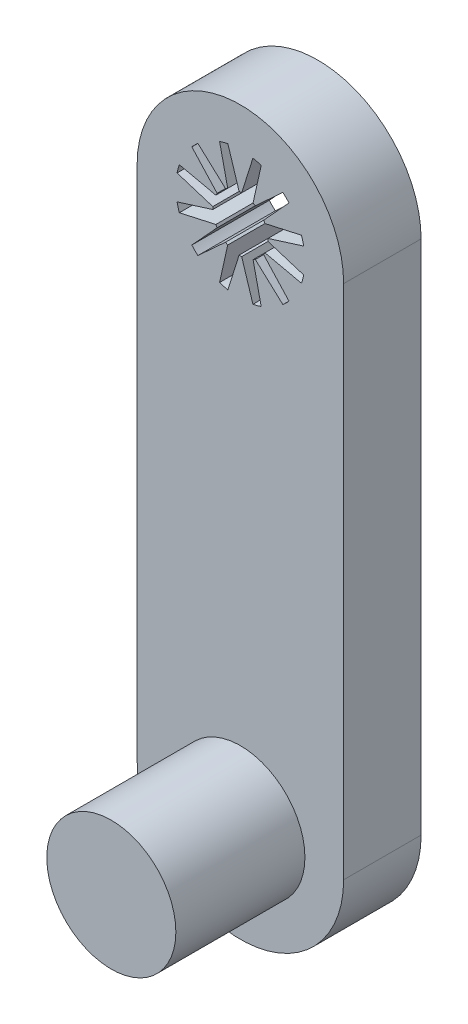
SolidWorks part; units mm, degrees
ref_plane "Front Plane" through (0, 0, 0) normal (1, 0, 0) x (0, 1, 0)
ref_plane "Top Plane" through (0, 0, 0) normal (0, 0, 1) x (0, 1, 0)
ref_plane "Right Plane" through (0, 0, 0) normal (0, 1, 0) x (-1, 0, 0)
sketch "Sketch1" plane through (0, 0, 0) normal (0, 0, 1) x (0, 1, 0)
  line L0 (-16.0299, -4.0821) -> (3.9701, -4.0821)
  line L1 (3.9701, 3.9179) -> (-16.0299, 3.9179)
  arc A0 (3.9701, -4.0821) -> (3.9701, 3.9179) centre (3.9701, -0.0821) ccw
  arc A1 (-16.0299, 3.9179) -> (-16.0299, -4.0821) centre (-16.0299, -0.0821) ccw
  dimension "D1" = 4
  dimension "D2" = 20
extrude "Boss-Extrude1" add sketch "Sketch1" along normal blind 3
sketch "Sketch4" plane through (0, 0, 3) normal (0, 0, 1) x (0, -1, 0)
  circle A0 centre (-3.9701, 0.0821) radius 2.5
  dimension "D1" = 5
extrude "Cut-Extrude2" cut sketch "Sketch4" against normal up to next
sketch "Sketch5" plane through (0, 0, 3) normal (0, 0, 1) x (1, 0, 0)
  line L0 (0.0821, 6.4701) -> (0.0821, 1.4701) construction
  line L1 (-0.4179, 1.4701) -> (0.5821, 1.4701)
  line L3 (0.0321, 2.9011) -> (0.1321, 2.9011)
  line L5 (-0.4179, 1.4701) -> (0.0321, 2.9011)
  line L6 (0.1321, 2.9011) -> (0.5821, 1.4701)
  line L7 (-1.6009, 2.0551) -> (-0.7349, 1.5551)
  line L8 (-0.4092, 3.0193) -> (-0.7349, 1.5551)
  line L9 (-1.6009, 2.0551) -> (-0.4958, 3.0693)
  line L10 (-0.4958, 3.0693) -> (-0.4092, 3.0193)
  line L11 (-2.333, 3.1532) -> (-1.833, 2.2871)
  line L12 (-0.8188, 3.3923) -> (-1.833, 2.2871)
  line L13 (-2.333, 3.1532) -> (-0.8688, 3.4789)
  line L14 (-0.8688, 3.4789) -> (-0.8188, 3.3923)
  line L15 (-2.4179, 4.4701) -> (-2.4179, 3.4701)
  line L16 (-0.987, 3.9201) -> (-2.4179, 3.4701)
  line L17 (-2.4179, 4.4701) -> (-0.987, 4.0201)
  line L18 (-0.987, 4.0201) -> (-0.987, 3.9201)
  line L19 (-1.833, 5.6532) -> (-2.333, 4.7871)
  line L20 (-0.8688, 4.4614) -> (-2.333, 4.7871)
  line L21 (-1.833, 5.6532) -> (-0.8188, 4.548)
  line L22 (-0.8188, 4.548) -> (-0.8688, 4.4614)
  line L23 (-0.7349, 6.3852) -> (-1.6009, 5.8852)
  line L24 (-0.4958, 4.871) -> (-1.6009, 5.8852)
  line L25 (-0.7349, 6.3852) -> (-0.4092, 4.921)
  line L26 (-0.4092, 4.921) -> (-0.4958, 4.871)
  line L27 (0.5821, 6.4701) -> (-0.4179, 6.4701)
  line L28 (0.0321, 5.0392) -> (-0.4179, 6.4701)
  line L29 (0.5821, 6.4701) -> (0.1321, 5.0392)
  line L30 (0.1321, 5.0392) -> (0.0321, 5.0392)
  line L31 (1.7651, 5.8852) -> (0.8991, 6.3852)
  line L32 (0.5733, 4.921) -> (0.8991, 6.3852)
  line L33 (1.7651, 5.8852) -> (0.6599, 4.871)
  line L34 (0.6599, 4.871) -> (0.5733, 4.921)
  line L35 (2.4972, 4.7871) -> (1.9972, 5.6532)
  line L36 (0.9829, 4.548) -> (1.9972, 5.6532)
  line L37 (2.4972, 4.7871) -> (1.0329, 4.4614)
  line L38 (1.0329, 4.4614) -> (0.9829, 4.548)
  line L39 (2.5821, 3.4701) -> (2.5821, 4.4701)
  line L40 (1.1512, 4.0201) -> (2.5821, 4.4701)
  line L41 (2.5821, 3.4701) -> (1.1512, 3.9201)
  line L42 (1.1512, 3.9201) -> (1.1512, 4.0201)
  line L43 (1.9972, 2.2871) -> (2.4972, 3.1532)
  line L44 (1.0329, 3.4789) -> (2.4972, 3.1532)
  line L45 (1.9972, 2.2871) -> (0.9829, 3.3923)
  line L46 (0.9829, 3.3923) -> (1.0329, 3.4789)
  line L47 (0.8991, 1.5551) -> (1.7651, 2.0551)
  line L48 (0.6599, 3.0693) -> (1.7651, 2.0551)
  line L49 (0.8991, 1.5551) -> (0.5733, 3.0193)
  line L50 (0.5733, 3.0193) -> (0.6599, 3.0693)
  circle A0 centre (0.0821, 3.9701) radius 2.5 construction
  point P7 (0.0821, 2.9011)
  point P10 (0.0821, 1.4701)
  point P58 (0.0821, 3.9701)
  dimension "D1" = 1
  dimension "D2" = 0.1
  dimension "D3" = 1.5
  dimension "D4" = 12
extrude "Boss-Extrude4" add sketch "Sketch5" against normal blind 3
sketch "Sketch6" plane through (0, 0, 3) normal (0, 0, 1) x (1, 0, 0)
  circle A0 centre (0.0821, -16.0299) radius 2.5
  dimension "D1" = 5
extrude "Boss-Extrude5" add sketch "Sketch6" along normal blind 5
